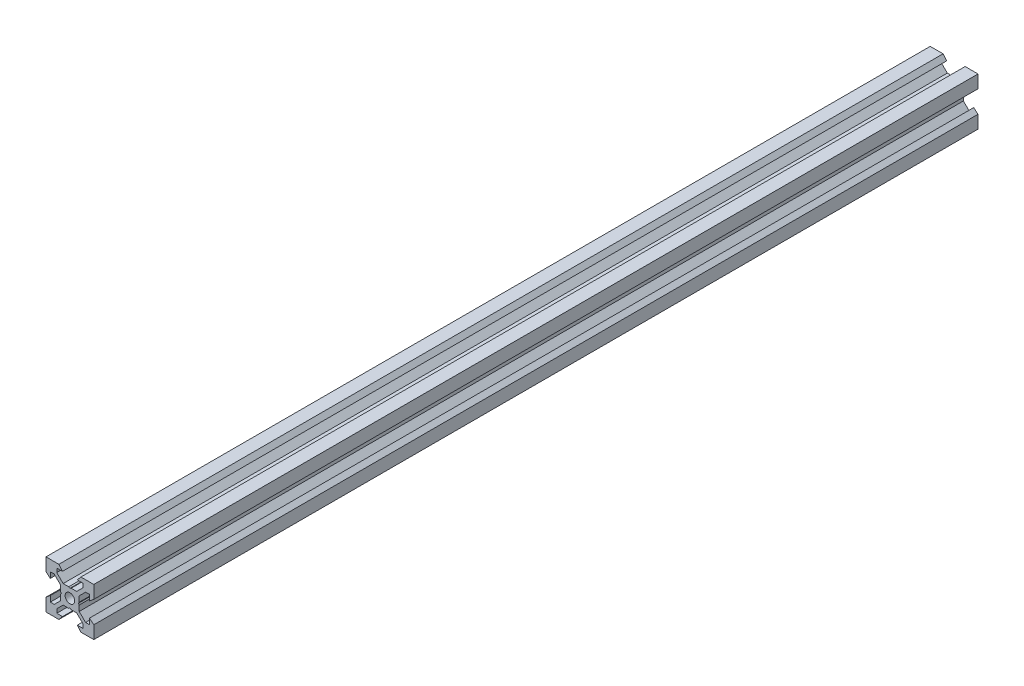
SolidWorks part; units mm, degrees
ref_plane "Front Plane" through (0, 0, 0) normal (0, 0, 1) x (1, 0, 0)
ref_plane "Top Plane" through (0, 0, 0) normal (0, 1, 0) x (1, 0, 0)
ref_plane "Right Plane" through (0, 0, 0) normal (1, 0, 0) x (0, 0, -1)
sketch "Sketch1" plane through (0, 0, 0) normal (0, 0, 1) x (1, 0, 0)
  line L0 (10, 10) -> (4.6104, 10) construction
  line L1 (10, 10) -> (10, 4.6104) construction
  line L2 (10, -10) -> (10, -4.6104) construction
  line L3 (10, -10) -> (4.6104, -10) construction
  line L4 (10, 10) -> (10, 4.6104)
  line L5 (6.5607, 5.5) -> (8.2, 5.5)
  line L6 (5.5, 8.2) -> (5.5, 6.5607)
  line L7 (10, 10) -> (4.6104, 10)
  line L8 (10, 10) -> (10, 4.6104)
  line L9 (6.5607, 5.5) -> (3.9, 2.8393)
  line L10 (5.5, 6.5607) -> (2.8393, 3.9)
  line L11 (10, 4.6104) -> (8.2, 3.1)
  line L12 (4.6104, 10) -> (3.1, 8.2)
  line L13 (8.2, 3.1) -> (8.2, 5.5)
  line L14 (3.1, 8.2) -> (5.5, 8.2)
  line L15 (-6.5607, 5.5) -> (-8.2, 5.5)
  line L16 (6.5607, -5.5) -> (8.2, -5.5)
  line L17 (3.1, -8.2) -> (5.5, -8.2)
  line L18 (8.2, -3.1) -> (8.2, -5.5)
  line L19 (4.6104, -10) -> (3.1, -8.2)
  line L20 (10, -4.6104) -> (8.2, -3.1)
  line L21 (0.5196, -3.9) -> (0, -3.6)
  line L22 (0.5196, 3.9) -> (0, 3.6)
  line L23 (3.6, 0) -> (3.9, -0.5196)
  line L24 (3.9, 0.5196) -> (3.6, 0)
  line L25 (3.9, 0.5196) -> (3.9, 2.8393)
  line L26 (2.8393, 3.9) -> (0.5196, 3.9)
  line L27 (3.9, -2.8393) -> (3.9, -0.5196)
  line L28 (2.8393, -3.9) -> (0.5196, -3.9)
  line L29 (5.5, -6.5607) -> (2.8393, -3.9)
  line L30 (6.5607, -5.5) -> (3.9, -2.8393)
  line L31 (10, -10) -> (10, -4.6104)
  line L32 (10, -10) -> (4.6104, -10)
  line L33 (5.5, -8.2) -> (5.5, -6.5607)
  line L34 (-6.5607, -5.5) -> (-8.2, -5.5)
  line L35 (10, -10) -> (10, -4.6104)
  line L36 (0, 0) -> (0, 8.2) construction
  line L37 (-10, -10) -> (-4.6104, -10) construction
  line L38 (-10, -10) -> (-10, -4.6104) construction
  line L39 (-10, 10) -> (-10, 4.6104) construction
  line L40 (-10, 10) -> (-4.6104, 10) construction
  line L41 (-10, -10) -> (-10, -4.6104)
  line L43 (-5.5, -8.2) -> (-5.5, -6.5607)
  line L44 (-10, -10) -> (-4.6104, -10)
  line L45 (-10, -10) -> (-10, -4.6104)
  line L46 (-6.5607, -5.5) -> (-3.9, -2.8393)
  line L47 (-5.5, -6.5607) -> (-2.8393, -3.9)
  line L48 (-2.8393, -3.9) -> (-0.5196, -3.9)
  line L49 (-3.9, -2.8393) -> (-3.9, -0.5196)
  line L50 (-2.8393, 3.9) -> (-0.5196, 3.9)
  line L51 (-3.9, 0.5196) -> (-3.9, 2.8393)
  line L52 (-3.9, 0.5196) -> (-3.6, 0)
  line L53 (-3.6, 0) -> (-3.9, -0.5196)
  line L54 (-0.5196, 3.9) -> (0, 3.6)
  line L55 (-0.5196, -3.9) -> (0, -3.6)
  line L56 (-10, -4.6104) -> (-8.2, -3.1)
  line L57 (-4.6104, -10) -> (-3.1, -8.2)
  line L58 (-8.2, -3.1) -> (-8.2, -5.5)
  line L59 (-3.1, -8.2) -> (-5.5, -8.2)
  line L60 (-10, -10) -> (10, -10) construction
  line L61 (-10, -10) -> (-10, 10) construction
  line L62 (-3.1, 8.2) -> (-5.5, 8.2)
  line L63 (-8.2, 3.1) -> (-8.2, 5.5)
  line L64 (-4.6104, 10) -> (-3.1, 8.2)
  line L65 (-10, 4.6104) -> (-8.2, 3.1)
  line L66 (-5.5, 6.5607) -> (-2.8393, 3.9)
  line L67 (-6.5607, 5.5) -> (-3.9, 2.8393)
  line L68 (-10, 10) -> (-10, 4.6104)
  line L69 (-10, 10) -> (-4.6104, 10)
  line L70 (-5.5, 8.2) -> (-5.5, 6.5607)
  line L71 (-10, 10) -> (10, 10) construction
  line L72 (-10, 10) -> (-10, 4.6104)
  line L73 (10, -10) -> (10, 10) construction
  line L74 (-10, -10) -> (10, 10) construction
  line L75 (-10, 10) -> (10, -10) construction
  circle A0 centre (0, 0) radius 2
  dimension "D7" = 4
  dimension "D1" = 20
  dimension "D2" = 5.3896
  dimension "D3" = 4.5
  dimension "D4" = 50
  dimension "D5" = 1.8
  dimension "D6" = 1.5104
  dimension "D8" = 5.5
  dimension "D9" = 120
  dimension "D10" = 0.3
  dimension "D11" = 2.3197
  dimension "D12" = 7.8
  dimension "D13" = 7.8
  dimension "D14" = 1.5
  dimension "D15" = 2.6607
extrude "Boss-Extrude1" add sketch "Sketch1" along normal mid plane 370 contours L70 L62 L64 L69 L68 L65 L63 L15 L67 L51 L52 L53 L49 L46 L34 L58 L56 L41 L44 L57 L59 L43 L47 L48 L55 L21 L28 L29 L33 L17 L19 L32 L31 L20 L18 L16 L30 L27 L23 L24 L25 L9 L5 L13 L11 L4 L7 L12 L14 L6 L10
